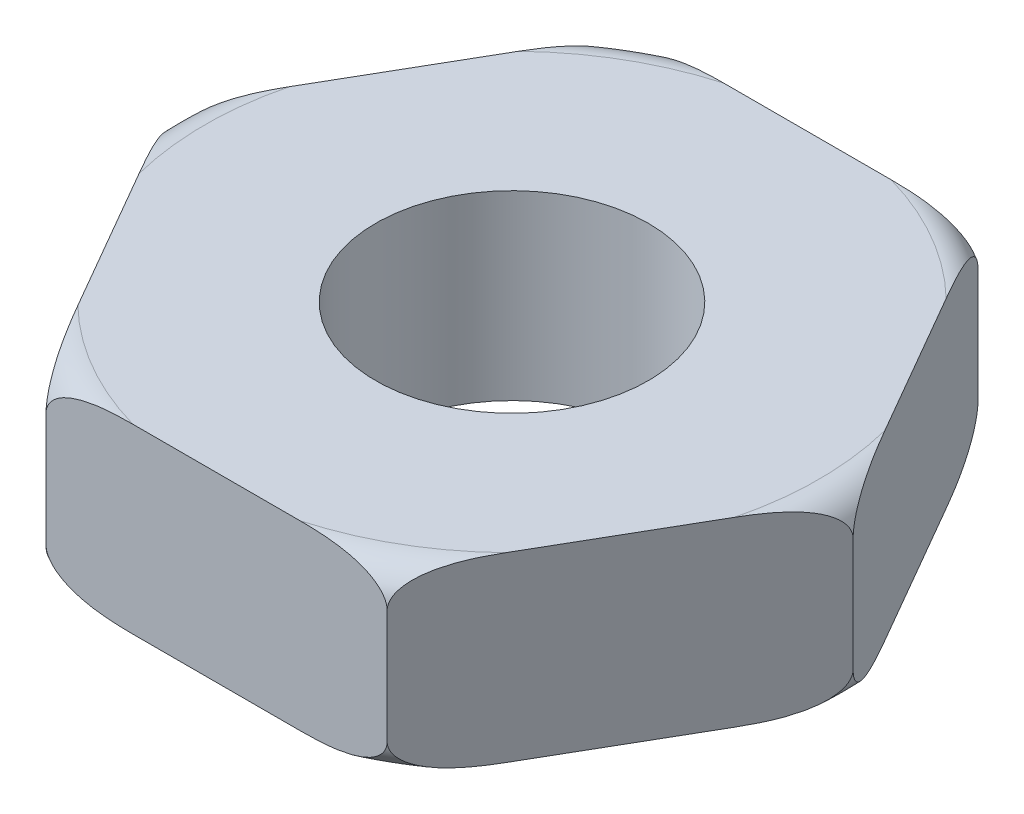
SolidWorks part; units mm, degrees
ref_plane "Front Plane" through (0, 0, 0) normal (0, 0, 1) x (1, 0, 0)
ref_plane "Top Plane" through (0, 0, 0) normal (0, 1, 0) x (1, 0, 0)
ref_plane "Right Plane" through (0, 0, 0) normal (1, 0, 0) x (0, 0, -1)
sketch "Sketch1" plane through (0, 0, 0) normal (0, 1, 0) x (1, 0, 0)
  line L0 (-15.0111, 0) -> (15.0111, 0) construction
  line L1 (7.5056, 13) -> (-7.5056, 13)
  line L2 (-7.5056, 13) -> (-15.0111, 0)
  line L3 (-15.0111, 0) -> (-7.5056, -13)
  line L4 (-7.5056, -13) -> (7.5056, -13)
  line L5 (7.5056, -13) -> (15.0111, 0)
  line L6 (15.0111, 0) -> (7.5056, 13)
  circle A0 centre (0, 0) radius 13 construction
  dimension "D1" = 26
extrude "Boss-Extrude1" add sketch "Sketch1" along normal blind 8
hole_wizard "Ø12.0mm Dowel Hole1" positions "Sketch3" profile "Sketch2" hole size "Ø12.0" standard "ANSI Metric" end condition through all
sketch "Sketch3" plane through (0, 0, 0) normal (0, -1, 0) x (-1, 0, 0)
  point P0 (0, 0)
sketch "Sketch2" plane through (0, 0, 0) normal (1, 0, 0) x (0, 0, -1)
  line L0 (0, 0) -> (0, 8)
  line L1 (0, 8) -> (6, 8)
  line L2 (6, 8) -> (6, 0)
  line L5 (6, 0) -> (0, 0)
  line L11 (0, -6.35) -> (0, 107.95) construction
  dimension "Thru Hole Dia." = 12
  dimension "Thru Hole Depth" = 8
sketch "Sketch4" plane through (0, 0, 0) normal (0, 0, 1) x (1, 0, 0)
  line L0 (0, 14.4064) -> (0, -3.2931) construction
  line L2 (20.3814, -9.5325) -> (20.3814, 1.5)
  line L4 (15.0111, 8) -> (15.0111, 0) construction
  line L6 (-15.0111, 4) -> (15.0111, 4) construction
  line L7 (-15.0111, 8) -> (-15.0111, 0) construction
  line L17 (13.5111, 8) -> (13.5111, 17.5325)
  line L18 (7.5056, 8) -> (15.0111, 8) construction
  line L19 (13.5111, 17.5325) -> (20.3814, 17.5325)
  line L20 (20.3814, 17.5325) -> (20.3814, 6.5)
  line L21 (20.3814, 6.5) -> (15.0111, 6.5)
  line L22 (13.5111, 8) -> (13.5111, 6.5) construction
  line L23 (13.5111, 6.5) -> (15.0111, 6.5) construction
  line L24 (13.5111, -9.5325) -> (20.3814, -9.5325)
  line L25 (13.5111, 0) -> (13.5111, -9.5325)
  line L26 (20.3814, 1.5) -> (15.0111, 1.5)
  arc A0 (13.5111, 8) -> (15.0111, 6.5) centre (13.5111, 6.5) cw
  arc A1 (13.5111, 0) -> (15.0111, 1.5) centre (13.5111, 1.5) ccw
  point P24 (-26.8849, 8.585)
  dimension "D1" = 1.5
revolve "Cut-Revolve2" cut sketch "Sketch4" angle 360 about L0
ref_plane "Plane1" through (0, 4, 0) normal (0, -1, 0) x (-1, 0, 0)
mirror "Mirror1" about plane through (0, 4, 0) normal (0, -1, 0) of "Cut-Revolve2"
